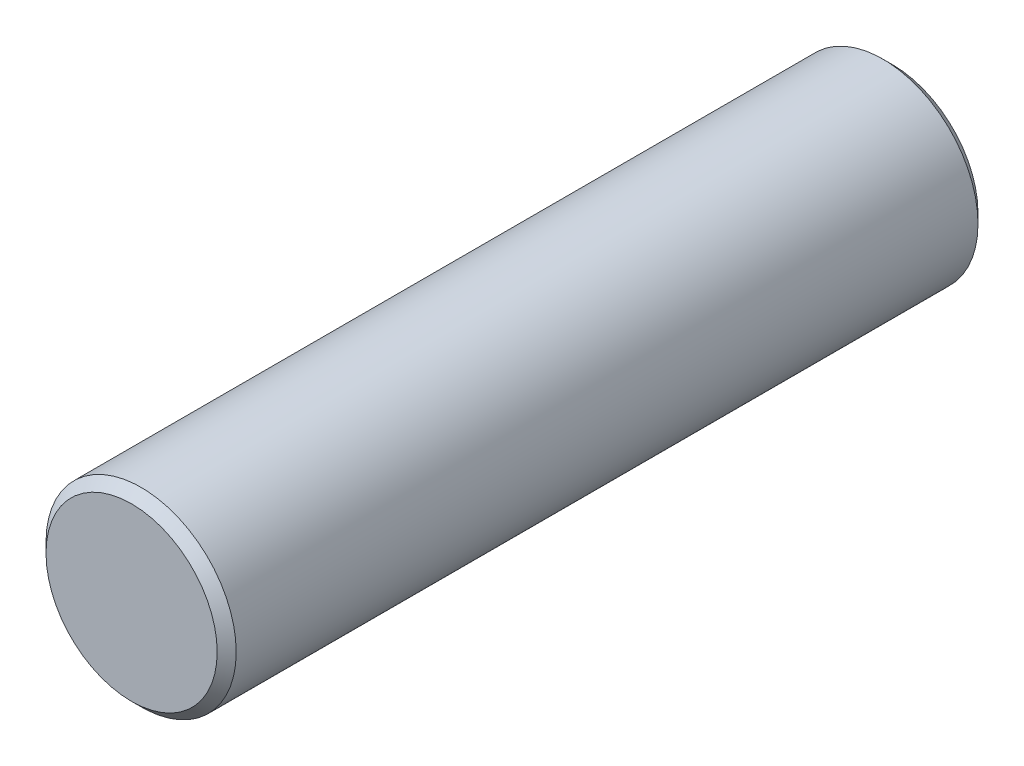
SolidWorks part; units mm, degrees
ref_plane "Front Plane" through (0, 0, 0) normal (0, 0, 1) x (1, 0, 0)
ref_plane "Top Plane" through (0, 0, 0) normal (0, 1, 0) x (1, 0, 0)
ref_plane "Right Plane" through (0, 0, 0) normal (1, 0, 0) x (0, 0, -1)
sketch "Sketch1" plane through (0, 0, 0) normal (0, 0, 1) x (1, 0, 0)
  circle A0 centre (0, 0) radius 1
  dimension "D1" = 2
extrude "Boss-Extrude2" add sketch "Sketch1" along normal mid plane 8
chamfer "Chamfer1" distance 0.1 angle 45 2 edges at (1, 0, -4) (1, 0, 4)
